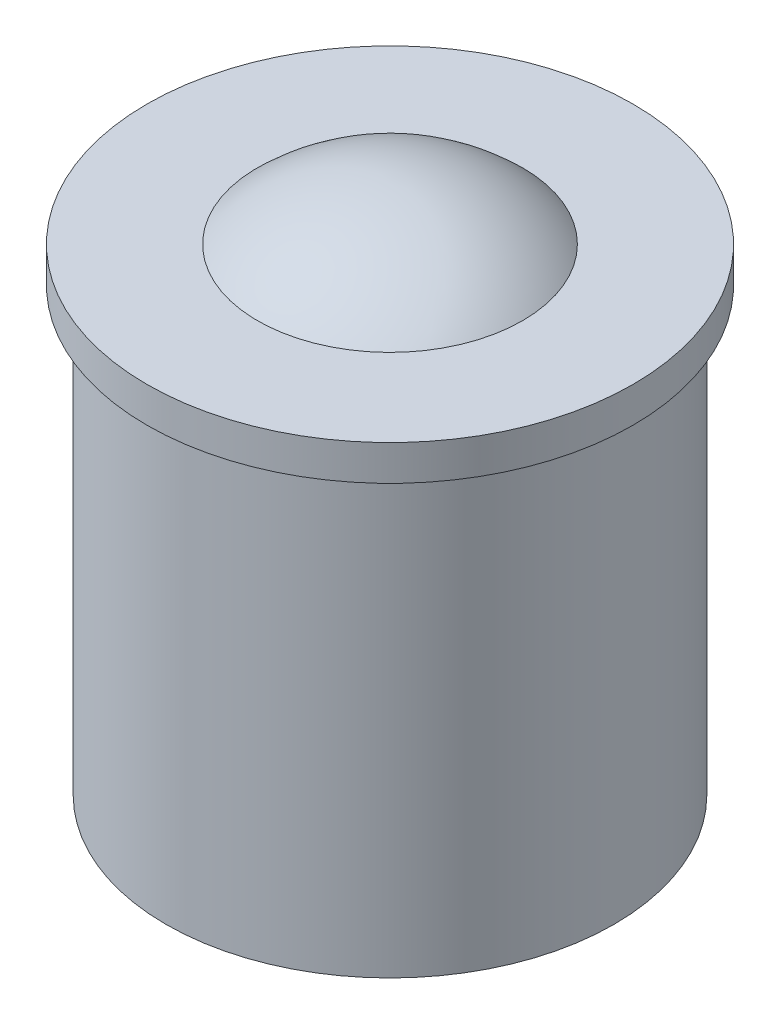
SolidWorks part; units mm, degrees
material "Plain Carbon Steel"
ref_plane "Front Plane" through (0, 0, 0) normal (0, 0, 1) x (1, 0, 0)
ref_plane "Top Plane" through (0, 0, 0) normal (0, 1, 0) x (1, 0, 0)
ref_plane "Right Plane" through (0, 0, 0) normal (1, 0, 0) x (0, 0, -1)
sketch "Sketch1" plane through (0, 0, 0) normal (0, 0, 1) x (1, 0, 0)
  line L0 (0, 0) -> (4.0259, 0)
  line L1 (4.0259, 0) -> (4.0259, 7.9375)
  line L2 (4.0259, 7.9375) -> (4.3656, 7.9375)
  line L3 (4.3656, 7.9375) -> (4.3656, 8.5725)
  line L4 (4.3656, 8.5725) -> (2.3813, 8.5725)
  line L5 (0, 0) -> (0, 9.525)
  line L6 (0, -5.8152) -> (0, 22.9924) construction
  arc A0 (2.3813, 8.5725) -> (0, 9.525) centre (0, 6.0722) ccw
  dimension "D6" = 4.7625
  dimension "D4" = 0.635
  dimension "D1" = 8.0518
  dimension "D2" = 9.525
  dimension "D3" = 8.7312
  dimension "D5" = 7.9375
revolve "Revolve1" add sketch "Sketch1" angle 360 about L6
